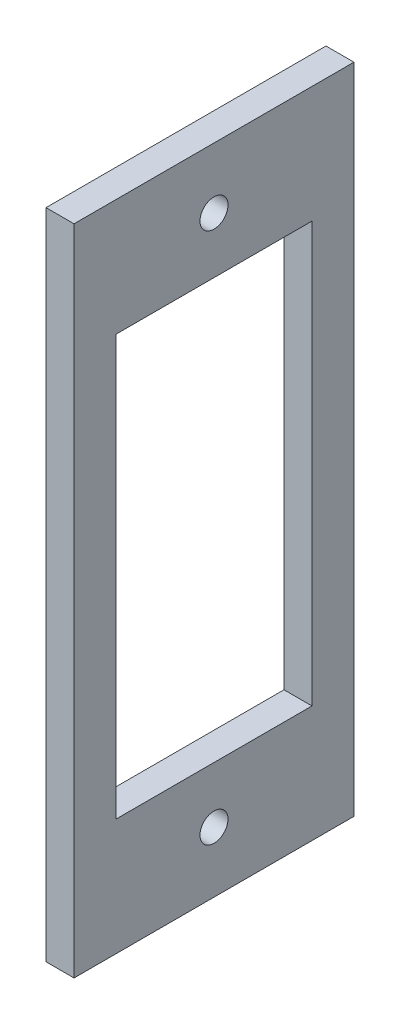
SolidWorks part; units mm, degrees
ref_plane "Front Plane" through (0, 0, 0) normal (0, 0, 1) x (1, 0, 0)
ref_plane "Top Plane" through (0, 0, 0) normal (0, 1, 0) x (1, 0, 0)
ref_plane "Right Plane" through (0, 0, 0) normal (1, 0, 0) x (0, 0, -1)
sketch "Sketch1" plane through (0, 0, 0) normal (1, 0, 0) x (0, 0, -1)
  line L1 (15, -35) -> (-15, -35)
  line L2 (15, -35) -> (15, 35)
  line L3 (15, 35) -> (-15, 35)
  line L4 (-15, -35) -> (-15, 35)
  line L5 (15, -35) -> (-15, 35) construction
  line L6 (15, 35) -> (-15, -35) construction
  point P0 (0, 0)
  dimension "D1" = 30
  dimension "D2" = 70
extrude "Boss-Extrude1" add sketch "Sketch1" along normal blind 3
sketch "Sketch2" plane through (3, 0, 0) normal (1, 0, 0) x (0, 0, -1)
  line L0 (0, 0) -> (15, 0) construction
  line L1 (10.5, -22.5) -> (-10.5, -22.5)
  line L2 (10.5, -22.5) -> (10.5, 22.5)
  line L3 (10.5, 22.5) -> (-10.5, 22.5)
  line L4 (-10.5, -22.5) -> (-10.5, 22.5)
  line L5 (10.5, -22.5) -> (-10.5, 22.5) construction
  line L6 (10.5, 22.5) -> (-10.5, -22.5) construction
  line L7 (15, -35) -> (15, 35) construction
  line L8 (0, 0) -> (0, 35) construction
  line L9 (15, 35) -> (-15, 35) construction
  line L10 (-15, -35) -> (15, -35) construction
  circle A0 centre (0, 28.5) radius 1.5
  circle A1 centre (0, -28.5) radius 1.5
  point P0 (0, 0)
  dimension "D3" = 3
  dimension "D5" = 15
  dimension "D1" = 45
  dimension "D2" = 21
  dimension "D4" = 6
extrude "Cut-Extrude1" cut sketch "Sketch2" against normal through all
